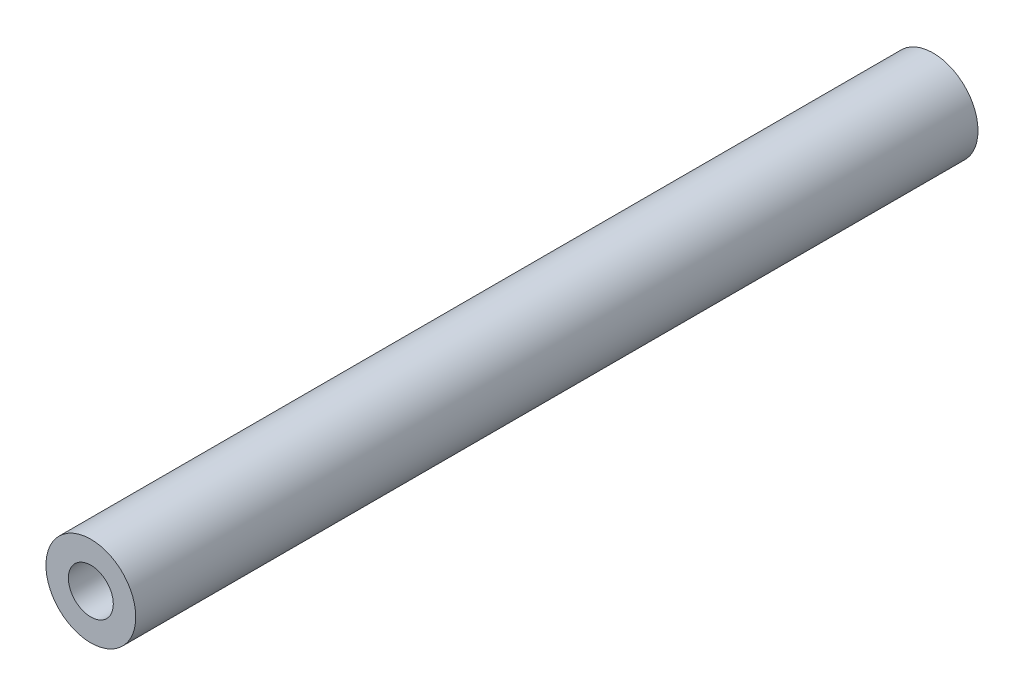
SolidWorks part; units mm, degrees
ref_plane "Front Plane" through (0, 0, 0) normal (0, 0, 1) x (1, 0, 0)
ref_plane "Top Plane" through (0, 0, 0) normal (0, 1, 0) x (1, 0, 0)
ref_plane "Right Plane" through (0, 0, 0) normal (1, 0, 0) x (0, 0, -1)
sketch "Sketch1" plane through (0, 0, 0) normal (0, 0, 1) x (1, 0, 0)
  circle A0 centre (0, 0) radius 4
  dimension "D1" = 8
extrude "Boss-Extrude1" add sketch "Sketch1" along normal mid plane 75
sketch "Sketch2" plane through (0, 0, 37.5) normal (0, 0, 1) x (1, 0, 0)
  circle A0 centre (0, 0) radius 2
  dimension "D1" = 4
extrude "Cut-Extrude1" cut sketch "Sketch2" against normal blind 4
mirror "Mirror1" about plane through (0, 0, 0) normal (0, 0, 1) of "Cut-Extrude1"
